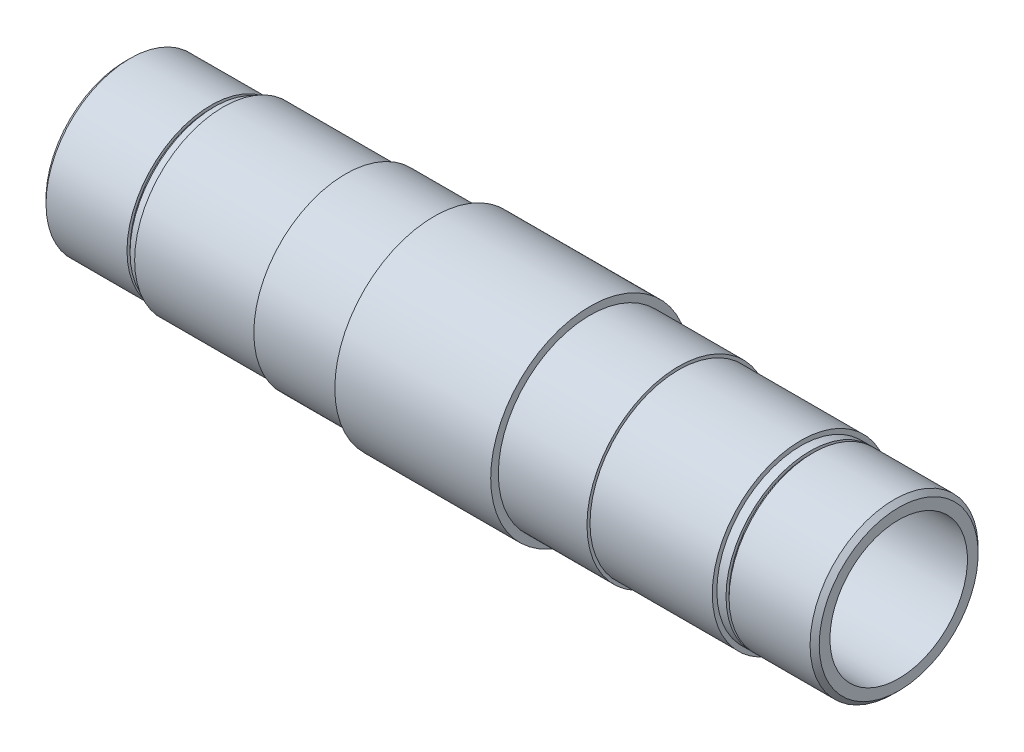
SolidWorks part; units mm, degrees
ref_plane "前视基准面" through (0, 0, 0) normal (0, 0, 1) x (1, 0, 0)
ref_plane "上视基准面" through (0, 0, 0) normal (0, 1, 0) x (1, 0, 0)
ref_plane "右视基准面" through (0, 0, 0) normal (1, 0, 0) x (0, 0, -1)
sketch "Sketch1" plane through (0, 0, 0) normal (0, 0, 1) x (1, 0, 0)
  line L0 (0, 0) -> (136.8229, 0) construction
  line L3 (0, 32.5) -> (-25.5, 32.5)
  line L4 (-25.5, 32.5) -> (-25.5, 30)
  line L5 (-25.5, 30) -> (-54.5, 30)
  line L13 (-54.5, 29) -> (-94.5, 29)
  line L15 (-54.5, 30) -> (-54.5, 29)
  line L16 (-94.5, 29) -> (-94.5, 27.5)
  line L21 (-126.5, 27.5) -> (-126.5, 22.5)
  line L22 (-126.5, 22.5) -> (0, 22.5)
  line L23 (0, 22.5) -> (0, 32.5)
  line L24 (-126.5, 27.5) -> (-98.5, 27.5)
  line L25 (-98.5, 27.5) -> (-98.5, 26.5)
  line L26 (-98.5, 26.5) -> (-97.5, 26.5)
  line L27 (-97.5, 26.5) -> (-97.5, 27.5)
  line L29 (-97.5, 27.5) -> (-94.5, 27.5)
  dimension "D1" = 65
  dimension "D2" = 25.5
  dimension "D3" = 60
  dimension "D4" = 58
  dimension "D5" = 29
  dimension "D6" = 40
  dimension "D7" = 32
  dimension "D10" = 45
  dimension "D11" = 1
  dimension "D12" = 1
  dimension "D13" = 28
  dimension "D14" = 55
revolve "Revolve1" add sketch "Sketch1" angle 360 about L0
mirror "Mirror1" about plane through (0, 0, 0) normal (1, 0, 0) of "Revolve1"
chamfer "Chamfer1" distance 1.5 angle 45 2 edges at (126.5, 0, 27.5) (-126.5, 0, 27.5)
